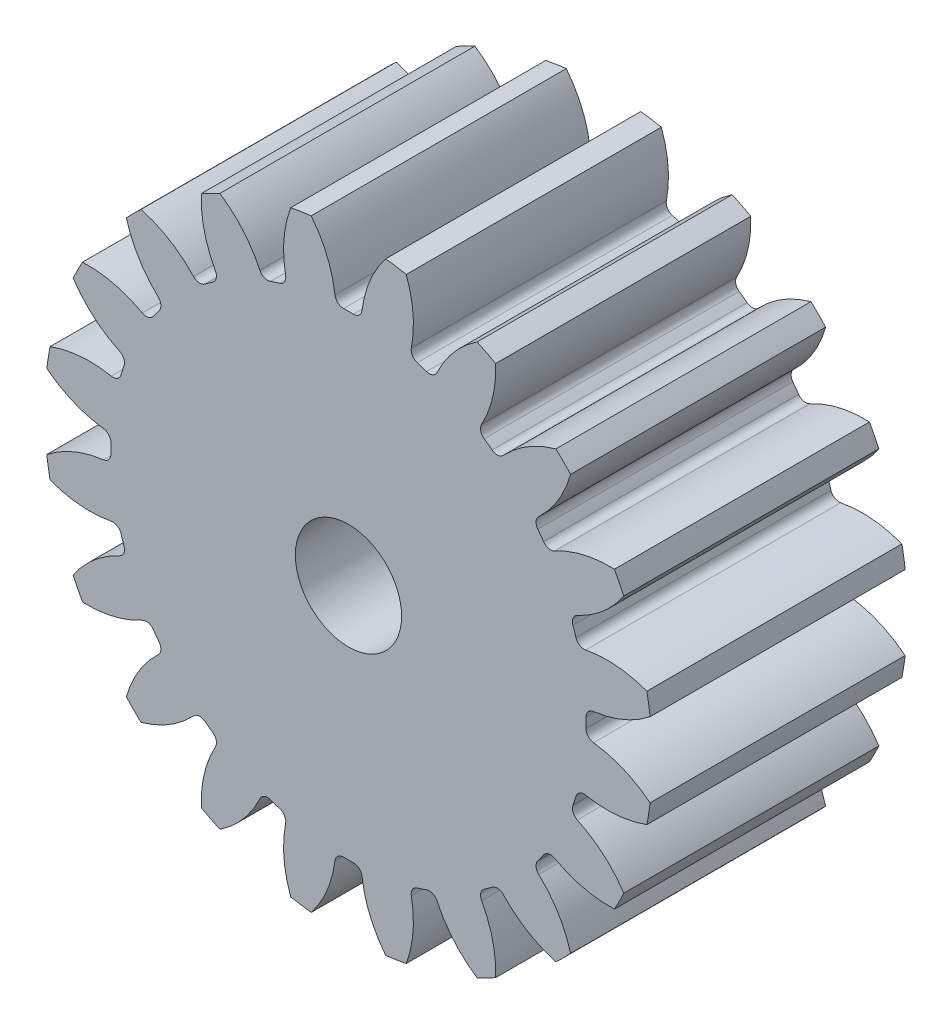
SolidWorks part; units mm, degrees
ref_plane "Front Plane" through (0, 0, 0) normal (0, 0, 1) x (1, 0, 0)
ref_plane "Top Plane" through (0, 0, 0) normal (0, 1, 0) x (1, 0, 0)
ref_plane "Right Plane" through (0, 0, 0) normal (1, 0, 0) x (0, 0, -1)
sketch "Sketch1" plane through (0, 0, 0) normal (0, 0, 1) x (1, 0, 0)
  circle A0 centre (0, 0) radius 6.5
  circle A1 centre (0, 0) radius 7.15
  circle A2 centre (0, 0) radius 5.59
  dimension "D1" = 13
  dimension "D2" = 14.3
  dimension "D3" = 1.56
extrude "Boss-Extrude1" add sketch "Sketch1" along normal mid plane 6 contours A1
sketch "Sketch2" plane through (0, 0, 0) normal (0, 0, 1) x (1, 0, 0)
  line L0 (0, 0) -> (0, 7.15) construction
  line L1 (0, -3.3) -> (0, 3.3) construction
  line L2 (-0.51, 6.48) -> (0.51, 6.48) construction
  line L3 (0, 0) -> (-0.3018, 5.5818) construction
  line L4 (0, 5.2785) -> (-0.919, 7.4435) construction
  line L5 (0, 0) -> (1.1185, 7.062) construction
  line L6 (0.51, 6.48) -> (1.5174, 6.3204) construction
  circle A0 centre (0, 0) radius 7.15 construction
  arc A1 (-1.1679, 7.4085) -> (-0.3018, 5.5818) centre (-2.9651, 5.4378) cw
  arc A2 (1.1679, 7.4085) -> (0.3018, 5.5818) centre (2.9651, 5.4378) ccw
  circle A3 centre (0, 0) radius 5.59 construction
  arc A4 (0.3018, 5.5818) -> (-0.3018, 5.5818) centre (0, 0) ccw
  circle A5 centre (0, 0) radius 7.15 construction
  circle A7 centre (0, 0) radius 6.5 construction
  circle A8 centre (0, 0) radius 7.5
  arc A9 (1.1679, 7.4085) -> (-1.1679, 7.4085) centre (0, 0) ccw
  dimension "D2" = 23
  dimension "D3" = 9
  dimension "D1" = 0.35
extrude "Cut-Extrude1" cut sketch "Sketch2" against normal through all both and the other way through all
fillet "Fillet1" radius 0.2 2 edges at (0.3018, 5.5818, 0) (-0.3018, 5.5818, 0)
pattern_circular "CirPattern1" count 20 over 360 about axis through (0, 0, 0) along (0, 0, 1) of "Cut-Extrude1", "Fillet1"
sketch "Sketch4" plane through (0, 0, 0) normal (1, 0, 0) x (0, 0, -1)
  line L0 (-3.3209, 0) -> (3.2965, 0) construction
  line L1 (3.3, 0) -> (-3.3, 0) construction
sketch "Sketch5" plane through (0, 0, -3) normal (0, 0, -1) x (-1, 0, 0)
  circle A0 centre (0, 0) radius 1.25
  dimension "D1" = 2.5
extrude "Cut-Extrude2" cut sketch "Sketch5" against normal blind 10
equation "\"Teeth\"= 20"
equation "\"PitchDiameter\"= 13"
equation "\"Module\"= ( \"PitchDiameter\" ) / \"Teeth\""
equation "\"D1@Sketch1\"=\"PitchDiameter\" "
equation "\"D2@Sketch1\"=(\"Teeth\" + 2) * \"Module\""
equation "\"D3@Sketch1\"= \"Module\" * ( IIF ( \"Module\" = > 1.25 , 2.25 , 2.4 ) )"
equation "\"D3@Sketch2\"=180 /\"Teeth\""
equation "\"D1@CirPattern1\"=\"Teeth\""
